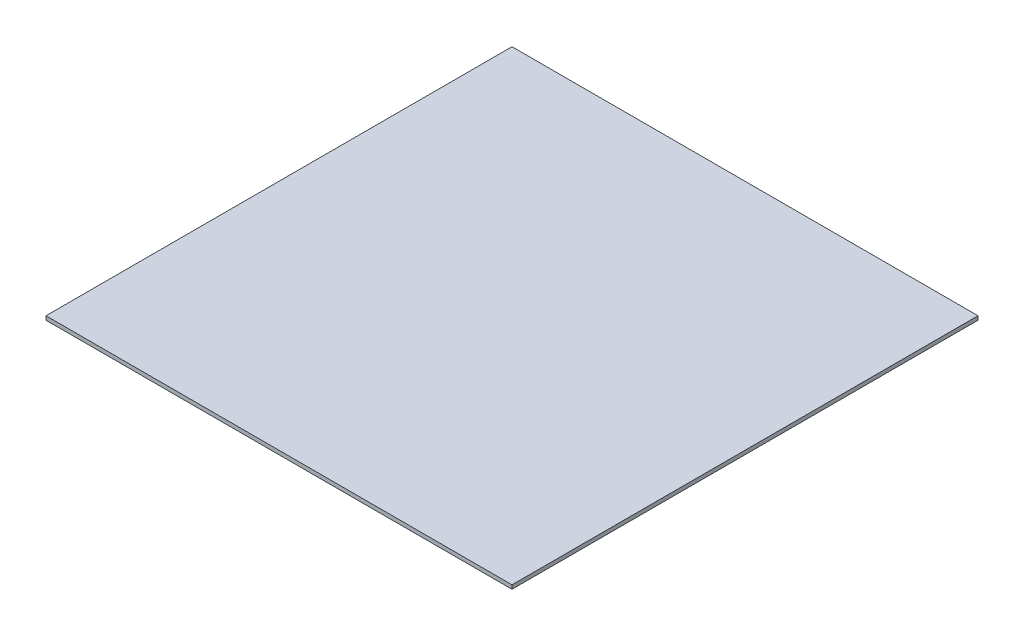
SolidWorks part; units mm, degrees
ref_plane "Front Plane" through (0, 0, 0) normal (0, 0, 1) x (1, 0, 0)
ref_plane "Top Plane" through (0, 0, 0) normal (0, 1, 0) x (1, 0, 0)
ref_plane "Right Plane" through (0, 0, 0) normal (1, 0, 0) x (0, 0, -1)
sketch "Sketch1" plane through (0, 0, 0) normal (0, 1, 0) x (1, 0, 0)
  line L1 (120, -120) -> (-120, -120)
  line L2 (120, -120) -> (120, 120)
  line L3 (120, 120) -> (-120, 120)
  line L4 (-120, -120) -> (-120, 120)
  line L5 (120, -120) -> (-120, 120) construction
  line L6 (120, 120) -> (-120, -120) construction
  point P0 (0, 0)
  dimension "D1" = 240
extrude "Boss-Extrude1" add sketch "Sketch1" along normal mid plane 2
